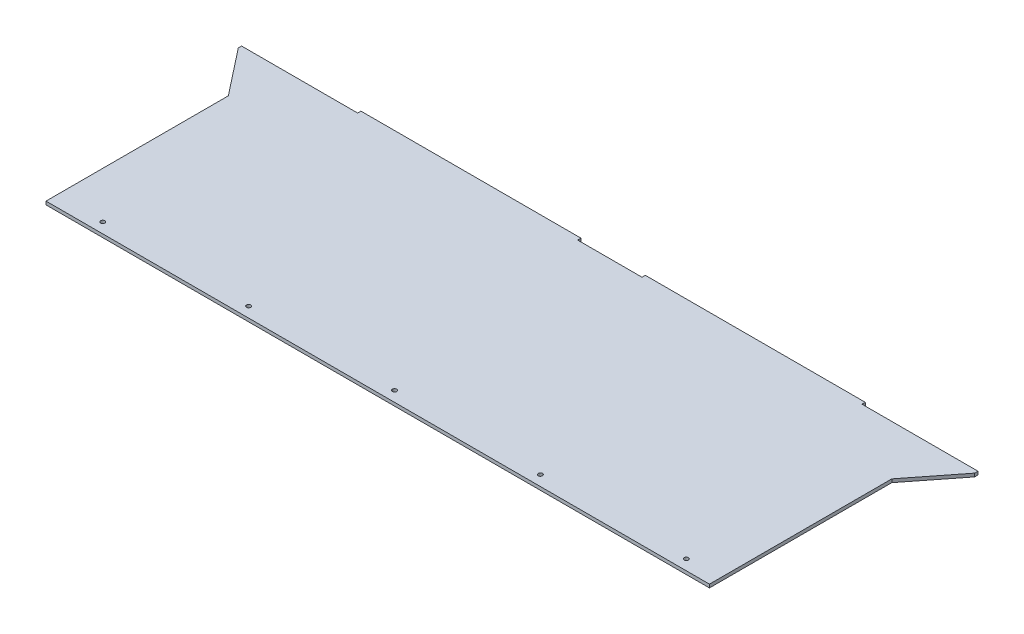
SolidWorks part; units mm, degrees
material "6061-T6 (SS)"
ref_plane "X-Y Datum" through (0, 0, 0) normal (0, 0, 1) x (1, 0, 0)
ref_plane "X-Z Datum" through (0, 0, 0) normal (0, 1, 0) x (1, 0, 0)
ref_plane "Y-Z Datum" through (0, 0, 0) normal (1, 0, 0) x (0, 0, -1)
sketch "Sketch1" plane through (0, 0, 0) normal (0, 1, 0) x (1, 0, 0)
  line L1 (-317.6778, 111.125) -> (317.6778, 111.125)
  line L2 (-317.6778, 111.125) -> (-317.6778, -111.125)
  line L3 (-317.6778, -111.125) -> (317.6778, -111.125)
  line L4 (317.6778, 111.125) -> (317.6778, -111.125)
  line L5 (-317.6778, 111.125) -> (317.6778, -111.125) construction
  line L6 (-317.6778, -111.125) -> (317.6778, 111.125) construction
  point P0 (0, 0)
  dimension "D1" = 635.3556
  dimension "D2" = 222.25
extrude "Boss-Extrude1" add sketch "Sketch1" along normal mid plane 3.175
sketch "Sketch2" plane through (0, 0, -111.125) normal (0, 0, -1) x (-1, 0, 0)
  line L0 (-241.4778, -1.5875) -> (-241.4778, 1.5875) construction
  line L1 (241.4778, -1.5875) -> (241.4778, 1.5875)
  line L2 (-241.4778, -1.5875) -> (-241.4778, 1.5875)
  line L3 (-241.4778, -1.5875) -> (-241.4778, 1.5875)
  line L4 (241.4778, -1.5875) -> (241.4778, 1.5875) construction
  line L5 (241.4778, -1.5875) -> (241.4778, 1.5875)
  line L20 (-317.6778, -1.5875) -> (317.6778, -1.5875) construction
  line L21 (-241.4778, -1.5875) -> (-30.8229, -1.5875)
  line L22 (30.8229, -1.5875) -> (241.4778, -1.5875)
  line L40 (30.8229, -1.5875) -> (30.8229, 1.5875)
  line L41 (30.8229, 1.5875) -> (241.4778, 1.5875)
  line L57 (-241.4778, 1.5875) -> (-30.8229, 1.5875)
  line L58 (-30.8229, 1.5875) -> (-30.8229, -1.5875)
  line M22 (-317.6778, -1.5875) -> (317.6778, -1.5875)
  line M24 (317.6778, 1.5875) -> (-317.6778, 1.5875)
extrude "Boss-Extrude2" add sketch "Sketch2" along normal blind 3.175 contours L58 L2 M24 M22 | L40 L1 M22 M24
sketch "Sketch3" plane through (0, 1.5875, 0) normal (0, 1, 0) x (1, 0, 0)
  line L0 (-317.6778, 111.125) -> (-352.6028, 111.125)
  line L1 (-352.6028, 111.125) -> (-352.6028, 107.95)
  line L2 (-352.6028, 107.95) -> (-317.6778, 63.5)
  line L3 (-317.6778, 111.125) -> (-317.6778, -111.125) construction
  line L16 (317.6778, -111.125) -> (317.6778, 111.125)
  line L17 (317.6778, 111.125) -> (241.4778, 111.125)
  line L18 (241.4778, 111.125) -> (241.4778, 114.3)
  line L19 (30.8229, 114.3) -> (30.8229, 111.125)
  line L20 (30.8229, 111.125) -> (-30.8229, 111.125)
  line L21 (-30.8229, 111.125) -> (-30.8229, 114.3)
  line L22 (-241.4778, 114.3) -> (-241.4778, 111.125)
  line L23 (-241.4778, 111.125) -> (-317.6778, 111.125)
  line L24 (241.4778, 114.3) -> (30.8229, 114.3)
  line L25 (241.4778, 114.3) -> (30.8229, 114.3)
  line L26 (-317.6778, 111.125) -> (-317.6778, -111.125)
  line L27 (-317.6778, -111.125) -> (317.6778, -111.125)
  line L38 (-317.6778, 111.125) -> (-317.6778, 63.5)
  line L40 (-30.8229, 114.3) -> (-241.4778, 114.3)
  line L41 (-30.8229, 114.3) -> (-241.4778, 114.3)
  line M26 (-317.6778, 111.125) -> (-317.6778, -111.125)
  dimension "D1" = 34.925
  dimension "D2" = 3.175
  dimension "D3" = 44.45
  dimension "D4" = 0
extrude "Boss-Extrude3" add sketch "Sketch3" against normal blind 3.175 contours L1 L2 L0 M26
mirror "Mirror1" about plane through (0, 0, 0) normal (1, 0, 0) of "Boss-Extrude3"
sketch "Sketch4" plane through (0, 1.5875, 0) normal (0, 1, 0) x (1, 0, 0)
  line L0 (-273.2278, -111.125) -> (-273.2278, -101.219)
  line L1 (-317.6778, -111.125) -> (317.6778, -111.125) construction
  line L2 (-273.2278, -101.219) -> (-317.6778, -101.219)
  line L3 (-317.6778, 63.5) -> (-317.6778, -111.125) construction
  circle A0 centre (-273.2278, -101.219) radius 2.025
extrude "Cut-Extrude1" cut sketch "Sketch4" against normal blind 10 contours L0 A0 L2 | L2 A0 L0
pattern_linear "LPattern1" count 5 spacing 139.7 along (1, 0, 0) of "Cut-Extrude1"
